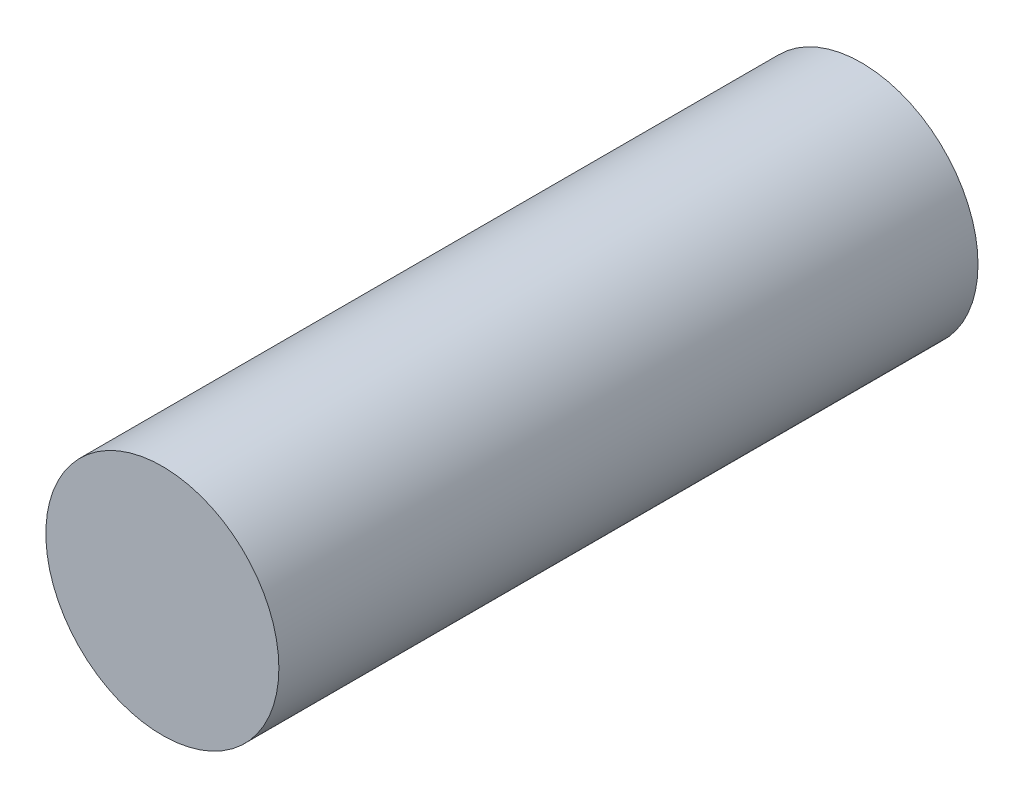
SolidWorks part; units mm, degrees
ref_plane "Plan de face" through (0, 0, 0) normal (0, 0, 1) x (1, 0, 0)
ref_plane "Plan de dessus" through (0, 0, 0) normal (0, 1, 0) x (1, 0, 0)
ref_plane "Plan de droite" through (0, 0, 0) normal (1, 0, 0) x (0, 0, -1)
sketch "Esquisse1" plane through (0, 0, 0) normal (0, 0, 1) x (1, 0, 0)
  circle A0 centre (0, 0) radius 3
  dimension "D1" = 6
extrude "Extrusion1" add sketch "Esquisse1" along normal blind 18
